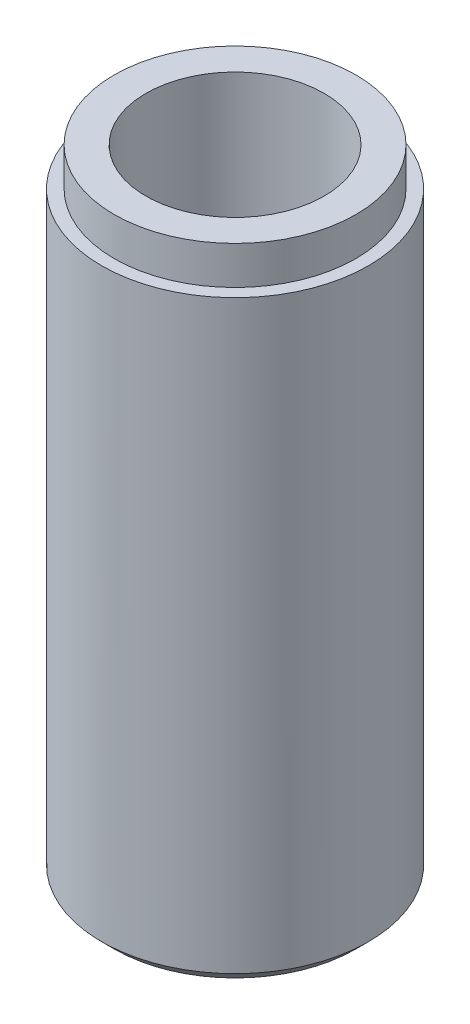
SolidWorks part; units mm, degrees
ref_plane "Плоскость1" through (0, 0, 0) normal (0, 0, 1) x (1, 0, 0)
ref_plane "Плоскость2" through (0, 0, 0) normal (0, 1, 0) x (1, 0, 0)
ref_plane "Плоскость3" through (0, 0, 0) normal (1, 0, 0) x (0, 0, -1)
sketch "Эскиз1" plane through (0, 0, 0) normal (0, 0, 1) x (1, 0, 0)
  line L0 (0, 0) -> (0, 98.5138) construction
  line L1 (7, 0) -> (7, 50)
  line L2 (7, 50) -> (10.4775, 50)
  line L5 (10.4775, 50) -> (10.4775, 0)
  line L6 (10.4775, 0) -> (7, 0)
  dimension "D1" = 14
  dimension "D2" = 50
  dimension "D4" = 20.955
revolve "Повернуть1" add sketch "Эскиз1" angle 360 about L0
cosmetic thread "Условное изображение резьбы2" parameters "D1"=35, "D2"=19
chamfer "Фаска1" distance 1 angle 45 1 edges at (0, 0, -10.4775)
sketch "Эскиз2" plane through (0, 50, 0) normal (0, 1, 0) x (1, 0, 0)
  circle A0 centre (0, 0) radius 9.5
  dimension "D1" = 19
extrude "Вытянуть1" cut sketch "Эскиз2" against normal blind 3 flip side to cut
